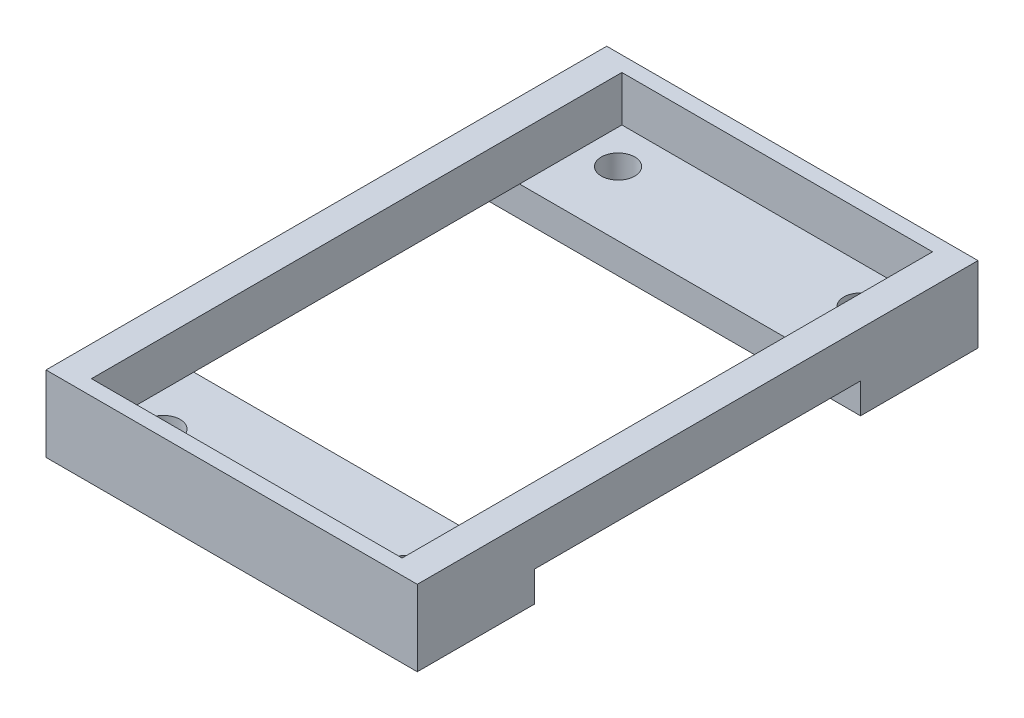
SolidWorks part; units mm, degrees
ref_plane "前视基准面" through (0, 0, 0) normal (0, 0, 1) x (1, 0, 0)
ref_plane "上视基准面" through (0, 0, 0) normal (0, 1, 0) x (1, 0, 0)
ref_plane "右视基准面" through (0, 0, 0) normal (1, 0, 0) x (0, 0, -1)
other "Configuration Table"
sketch "草图1" plane through (0, 0, 0) normal (0, 1, 0) x (1, 0, 0)
  line L1 (-10.25, 17.5) -> (10.25, 17.5)
  line L2 (-10.25, 17.5) -> (-10.25, -17.5)
  line L3 (-10.25, -17.5) -> (10.25, -17.5)
  line L4 (10.25, 17.5) -> (10.25, -17.5)
  line L5 (-10.25, 17.5) -> (10.25, -17.5) construction
  line L6 (-10.25, -17.5) -> (10.25, 17.5) construction
  point P0 (0, 0)
extrude "凸台-拉伸1" add sketch "草图1" along normal blind 2
sketch "草图2" plane through (0, 0, 0) normal (0, 1, 0) x (1, 0, 0)
  line L0 (10.25, 17.5) -> (-10.25, 17.5) construction
  line L1 (-12.25, -18.5) -> (12.25, -18.5)
  line L2 (-12.25, -18.5) -> (-12.25, 18.5)
  line L3 (-12.25, 18.5) -> (12.25, 18.5)
  line L4 (12.25, -18.5) -> (12.25, 18.5)
  line L5 (-12.25, -18.5) -> (12.25, 18.5) construction
  line L6 (-12.25, 18.5) -> (12.25, -18.5) construction
  line L7 (10.25, -17.5) -> (10.25, 17.5) construction
  line L9 (-10.25, 17.5) -> (10.25, 17.5)
  line L10 (-10.25, 17.5) -> (-10.25, -17.5)
  line L11 (-10.25, -17.5) -> (10.25, -17.5)
  line L12 (10.25, 17.5) -> (10.25, -17.5)
  line L13 (-10.25, 17.5) -> (10.25, -17.5) construction
  line L14 (-10.25, -17.5) -> (10.25, 17.5) construction
  point P0 (0, 0)
  point P10 (0, 0)
  dimension "D1" = 1
  dimension "D2" = 2
extrude "凸台-拉伸2" add sketch "草图2" along normal blind 5
sketch "草图3" plane through (0, 0, 0) normal (0, -1, 0) x (1, 0, 0)
  line L1 (-8, 15) -> (8, 15) construction
  line L2 (-8, 15) -> (-8, -15) construction
  line L3 (-8, -15) -> (8, -15) construction
  line L4 (8, 15) -> (8, -15) construction
  line L5 (-8, 15) -> (8, -15) construction
  line L6 (-8, -15) -> (8, 15) construction
  circle A0 centre (-8, 15) radius 1.1
  circle A1 centre (8, 15) radius 1.1
  circle A2 centre (8, -15) radius 1.1
  circle A3 centre (-8, -15) radius 1.1
  point P0 (0, 0)
extrude "切除-拉伸1" cut sketch "草图3" against normal through all
sketch "草图4" plane through (0, 0, 0) normal (0, -1, 0) x (1, 0, 0)
  line L5 (-12.25, 0) -> (0, 0) construction
  line L6 (-12.25, 10.75) -> (12.25, 10.75)
  line L8 (-12.25, -18.5) -> (-12.25, 18.5) construction
  line L9 (-12.25, 10.75) -> (-12.25, -10.75)
  line L10 (12.25, 18.5) -> (12.25, -18.5) construction
  line L11 (12.25, 10.75) -> (12.25, -10.75)
  line L12 (12.25, -10.75) -> (-12.25, -10.75)
  point P0 (0, 0)
  dimension "D3" = 21.5
extrude "切除-拉伸4" cut sketch "草图4" against normal up to surface (2 mm away) up to face at (-8, 2, -13.9)
